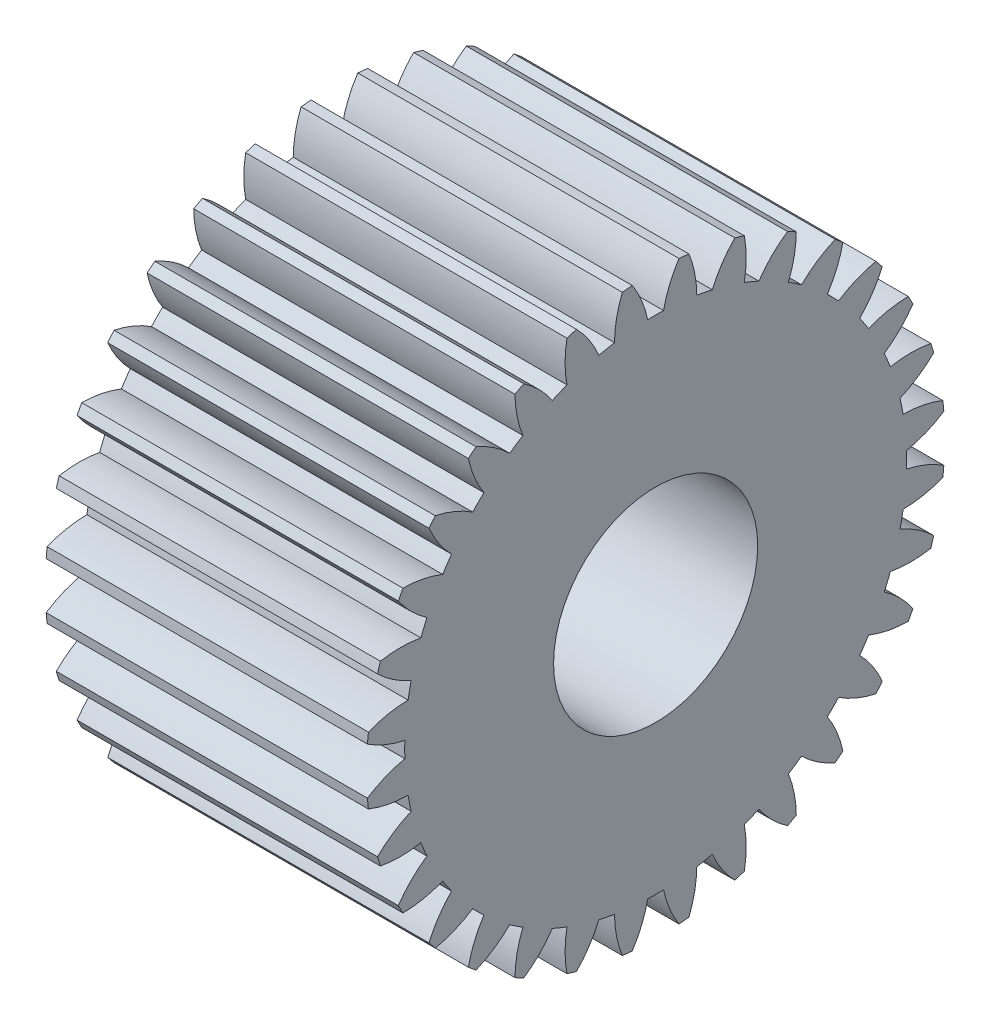
SolidWorks part; units mm, degrees
ref_plane "Plane1" through (0, 0, 0) normal (0, 0, 1) x (1, 0, 0)
ref_plane "Plane2" through (0, 0, 0) normal (0, 1, 0) x (1, 0, 0)
ref_plane "Plane3" through (0, 0, 0) normal (1, 0, 0) x (0, 0, -1)
other "Configuration Table"
sketch "HoldingSke" plane through (0, 0, 0) normal (0, 1, 0) x (1, 0, 0)
  line L0 (0, 0) -> (516.9701, -323.0388)
  line L1 (-15, 0) -> (100, 0) construction
  line L2 (0, 0) -> (-2.1039, 2.3779)
  line L3 (0, 0) -> (-11.863, 4.5341)
  line L4 (0, 0) -> (7.3237, 4.5764)
  line L5 (0, 0) -> (-47.5972, -17.7524)
  line L6 (0, 0) -> (-16.5708, -11.1804)
  line L7 (-2.1039, 2.3779) -> (8.8308, 51.9871)
  line L8 (-76.2, 54.61) -> (-61.976, 54.61)
  line L9 (-71.009, 38.7566) -> (-53.1078, 45.2721)
  line L10 (-76.2, 71.12) -> (104.1128, 71.12)
  line L11 (0, 0) -> (-19.9898, 0)
  line L12 (-76.2, 101.6) -> (-76.1573, 101.6)
  line L13 (24.9733, 27.94) -> (52.9518, 28.4284)
  line L14 (24.9733, 27.94) -> (25.0241, 27.9398)
  line L15 (24.9733, 27.94) -> (100.4021, 29.52)
  circle A0 centre (0, 0) radius 6.35
  circle A1 centre (0, 0) radius 15.6125
  circle A2 centre (0, 0) radius 38.1
  circle A3 centre (0, 0) radius 6.35
  dimension "MHD" = 31.2251
  dimension "Hub_dia" = 76.2
  dimension "Bore" = 12.7
  dimension "MBD" = 12.7
  dimension "Num_teeth" = 32
  dimension "Pitch" = 609.6
  dimension "Overall_len" = 50.8
  dimension "Show_teeth" = 32
  dimension "Thickness" = 19.9898
  dimension "OAL" = 50.8001
  dimension "T_dim" = 14.224
  dimension "Ap" = 20
  dimension "H" = 19.05
  dimension "Pitch_radius" = 180.3128
  dimension "Width" = 19.9898
  dimension "Backlash" = 0.0427
  dimension "Addendum_fac" = 1
  dimension "Dedendum_fac" = 1.2
  dimension "Clearance_fac" = 0.2
  dimension "Dedendum_add" = 0.0508
sketch "BasProSke" plane through (0, 0, 0) normal (0, 1, 0) x (1, 0, 0)
  line L0 (-10, 0) -> (60, 0) construction
  line L1 (0, 0) -> (0, 17.9917)
  line L2 (0, 0) -> (19.9898, 0)
  line L3 (19.9898, 0) -> (19.9898, 17.9917)
  line L4 (19.9898, 17.9917) -> (0, 17.9917)
  dimension "Thickness" = 19.9898
  dimension "Diameter" = 35.9833
revolve "Base-Revolve" add sketch "BasProSke" angle 360 about L0
sketch "TooCutSke" plane through (0, 0, 0) normal (1, 0, 0) x (0, 0, -1)
  line L1 (0, 0) -> (0, 107) construction
  line L2 (0, 0) -> (-0.9055, 16.9091) construction
  line L3 (0, 0) -> (-3.3162, 33.67) construction
  line L4 (-0.9055, 16.9091) -> (-1.6581, 16.835) construction
  arc A0 (0.4936, 15.6047) -> (-0.4936, 15.6047) centre (0, 0) ccw
  arc A1 (1.4712, 17.9569) -> (-1.4712, 17.9569) centre (0, 0) ccw
  circle A2 centre (0, 0) radius 16.9333 construction
  circle A3 centre (0, 0) radius 15.9121 construction
  arc A4 (-0.4936, 15.6047) -> (-1.4712, 17.9569) centre (-7.1255, 14.2276) ccw
  arc A5 (1.4712, 17.9569) -> (0.4936, 15.6047) centre (7.1255, 14.2276) ccw
  dimension "Root_dia" = 31.2251
  dimension "Overcut_dia" = 36.0341
  dimension "Pitch_dia" = 33.8667
  dimension "Base_dia" = 31.8243
  dimension "Flank_rad" = 6.7733
  dimension "Half_ang" = 5.625
  dimension "Half_CT" = 0.7562
extrude "ToothCut" cut sketch "TooCutSke" along normal through all
fillet "Breaks" [suppressed] radius 0.0212
fillet "RootFillets" [suppressed] radius 0.2625
pattern_circular "TeethCuts" count 32 every 11.25 about axis through (-10, 0, 0) along (1, 0, 0) of "ToothCut", "RootFillets", "Breaks"
sketch "HubNeaOneSke" plane through (0, 0, 0) normal (-1, 0, 0) x (0, 0, 1)
  circle A0 centre (0, 0) radius 15.6125
  dimension "Diameter" = 31.2251
extrude "HubNearOne" [suppressed] add sketch "HubNeaOneSke" along normal blind 30.8103
sketch "HubNeaBotSke" plane through (0, 0, 0) normal (-1, 0, 0) x (0, 0, 1)
  circle A0 centre (0, 0) radius 15.6125
  dimension "Diameter" = 31.2251
extrude "HubNearBoth" [suppressed] add sketch "HubNeaBotSke" along normal blind 15.4051
ref_plane "FarPln" through (19.9898, 0, 0) normal (1, 0, 0) x (0, 0, -1)
sketch "HubFarSke" plane through (19.9898, 0, 0) normal (1, 0, 0) x (0, 0, -1)
  circle A0 centre (0, 0) radius 15.6125
  dimension "Diameter" = 31.2251
extrude "HubFar" [suppressed] add sketch "HubFarSke" along normal blind 15.4051
sketch "BorSke" plane through (0, 0, 0) normal (1, 0, 0) x (0, 0, -1)
  circle A0 centre (0, 0) radius 6.35
  dimension "Diameter" = 12.7
extrude "Bore" cut sketch "BorSke" along normal mid plane 101.6001
sketch "KeySke" plane through (0, 0, 0) normal (1, 0, 0) x (0, 0, -1)
  line L0 (-1.5875, 0) -> (-1.5875, 7.874)
  line L1 (-1.5875, 7.874) -> (1.5875, 7.874)
  line L2 (1.5875, 7.874) -> (1.5875, 0)
  line L3 (0, 0) -> (0, 34) construction
  line L4 (-1.5875, 0) -> (1.5875, 0)
  dimension "Offset" = 7.874
  dimension "Width" = 3.175
extrude "Keyway" [suppressed] cut sketch "KeySke" along normal mid plane 101.6001
pattern_circular "Keyway2" [suppressed] count 2 every 90 about axis through (-10, 0, 0) along (1, 0, 0)
equation "' \"Pitch@HoldingSke\" = 4"
equation "' \"Num_teeth@HoldingSke\" = 12"
equation "' \"Ap@HoldingSke\" =  20"
equation "' \"Ap@HoldingSke\" = 20"
equation "' \"Width@HoldingSke\" = 0.5"
equation "' \"Hub_dia@HoldingSke\"= 1"
equation "' \"Hub_dia@HoldingSke\" = 1"
equation "' \"Overall_len@HoldingSke\" = 1.0"
equation "' \"Bore@HoldingSke\" = 0.75"
equation "' \"T_dim@HoldingSke\" = 0.85"
equation "' \"Width@KeySke\" = 0.25"
equation "' \"Show_teeth@HoldingSke\" = 13"
equation "' \"Backlash@HoldingSke\" = 0.009"
equation "' \"Addendum_fac@HoldingSke\" = 1.0"
equation "' \"Dedendum_fac@HoldingSke\" = 1.25"
equation "' \"Dedendum_add@HoldingSke\" = 0.00005"
equation "' \"Clearance_fac@HoldingSke\" = 0.25"
equation "' \"Pitch@HoldingSke\" = 0.5"
equation "' \"Num_teeth@HoldingSke\" = 23"
equation "' \"Show_teeth@HoldingSke\" = 23"
equation "' \"Backlash@HoldingSke\" = 0.0375"
equation "\"Overcut_dia@TooCutSke\" = (\"Num_teeth@HoldingSke\" + 2 * \"Addendum_fac@HoldingSke\") / \"Pitch@HoldingSke\" + 0.002"
equation "\"Pitch_dia@TooCutSke\" = \"Num_teeth@HoldingSke\" / \"Pitch@HoldingSke\""
equation "\"Base_dia@TooCutSke\" = \"Num_teeth@HoldingSke\" / \"Pitch@HoldingSke\" * cos((\"Ap@HoldingSke\"  * 3.14159265 / 180))"
equation "\"Root_dia@TooCutSke\" = (\"Num_teeth@HoldingSke\" + 2) / \"Pitch@HoldingSke\" - 2 * (\"Addendum_fac@HoldingSke\" + \"Dedendum_fac@HoldingSke\") / \"Pitch@HoldingSke\" - \"Dedendum_add@HoldingSke\" * 2"
equation "\"Half_ang@TooCutSke\" = 180 / \"Num_teeth@HoldingSke\""
equation "\"Half_CT@TooCutSke\" = \"Num_teeth@HoldingSke\" / \"Pitch@HoldingSke\" * sin((3.14159265 / 2 / \"Num_teeth@HoldingSke\")) / 2 - 7 * \"Backlash@HoldingSke\" / 4"
equation "\"Flank_rad@TooCutSke\" = \"Num_teeth@HoldingSke\" / \"Pitch@HoldingSke\" / 5"
equation "\"Radius@RootFillets\" = \"Clearance_fac@HoldingSke\" / \"Pitch@HoldingSke\" + \"Dedendum_add@HoldingSke\""
equation "\"Break_rad@Breaks\" = 0.02 / \"Pitch@HoldingSke\""
equation "\"Thickness@HoldingSke\" = \"Width@HoldingSke\""
equation "\"OAL@HoldingSke\" = \"Thickness@HoldingSke\""
equation "\"MHD@HoldingSke\" = (\"Num_teeth@HoldingSke\" + 2) / \"Pitch@HoldingSke\" - 2 * (\"Addendum_fac@HoldingSke\" + \"Dedendum_fac@HoldingSke\")  / \"Pitch@HoldingSke\" - \"Dedendum_add@HoldingSke\" * 2"
equation "\"MBD@HoldingSke\" = (\"Num_teeth@HoldingSke\" + 2) / \"Pitch@HoldingSke\" - 2 * (\"Addendum_fac@HoldingSke\" + \"Dedendum_fac@HoldingSke\")  / \"Pitch@HoldingSke\" - \"Dedendum_add@HoldingSke\" * 2 - 0.002"
equation "\"MHD@HoldingSke\" = ((sgn( \"MHD@HoldingSke\" - \"Hub_dia@HoldingSke\" )-1)*( \"MHD@HoldingSke\" - \"Hub_dia@HoldingSke\" ))/-2+ \"Hub_dia@HoldingSke\""
equation "\"MBD@HoldingSke\" = ((sgn( \"MBD@HoldingSke\" - \"Bore@HoldingSke\" )-1)*( \"MBD@HoldingSke\" - \"Bore@HoldingSke\" ))/-2+ \"Bore@HoldingSke\""
equation "\"OAL@HoldingSke\" = ((sgn( \"OAL@HoldingSke\" - \"Overall_len@HoldingSke\" )+1)*( \"OAL@HoldingSke\" - \"Overall_len@HoldingSke\" ))/2 + \"Overall_len@HoldingSke\" + 0.000002"
equation "\"Num_teeth@TeethCuts\" = int( \"Show_teeth@HoldingSke\" ) + 1"
equation "\"Num_teeth@TeethCuts\" = ((sgn( \"Num_teeth@TeethCuts\" - \"Num_teeth@HoldingSke\" )-1)*( \"Num_teeth@TeethCuts\" - \"Num_teeth@HoldingSke\" ))/-2+ \"Num_teeth@HoldingSke\""
equation "\"Num_teeth@TeethCuts\" = ((sgn( \"Num_teeth@TeethCuts\" - 2.0)+1)*( \"Num_teeth@TeethCuts\" - 2.0))/2 +2.0"
equation "\"Angle@TeethCuts\" = 360.0 / \"Num_teeth@HoldingSke\""
equation "\"Diameter@BasProSke\" = (\"Num_teeth@HoldingSke\" + 2 * \"Addendum_fac@HoldingSke\") / \"Pitch@HoldingSke\""
equation "\"Thickness@BasProSke\"  = \"Thickness@HoldingSke\""
equation "' \"Fillet_rad@BasProSke\" =  \"Thickness@HoldingSke\" * 0.05"
equation "' \"Fillet_rad@BasProSke\" = \"Thickness@HoldingSke\" * 0.05"
equation "\"MHD@HoldingSke\" = ((sgn( \"MHD@HoldingSke\" - \"Root_dia@TooCutSke\" )-1)*( \"MHD@HoldingSke\" - \"Root_dia@TooCutSke\" ))/-2+ \"Root_dia@TooCutSke\""
equation "\"Diameter@HubNeaOneSke\" = \"MHD@HoldingSke\""
equation "\"Length@HubNearOne\" = \"OAL@HoldingSke\" - \"Thickness@BasProSke\""
equation "\"Diameter@HubNeaBotSke\" = \"MHD@HoldingSke\""
equation "\"Length@HubNearBoth\" = ( \"OAL@HoldingSke\" - \"Thickness@BasProSke\" ) / 2.0"
equation "\"Thickness@FarPln\" = \"Thickness@BasProSke\""
equation "\"Diameter@HubFarSke\" = \"MHD@HoldingSke\""
equation "\"Length@HubFar\" = ( \"OAL@HoldingSke\" - \"Thickness@BasProSke\" ) / 2.0"
equation "\"Diameter@BorSke\" = \"MBD@HoldingSke\""
equation "\"D1@Bore\" = \"OAL@HoldingSke\" * 2.0"
equation "\"D1@Keyway\" = \"OAL@HoldingSke\" * 2.0"
equation "\"Offset@KeySke\" = \"T_dim@HoldingSke\" - \"MBD@HoldingSke\" / 2.0"
